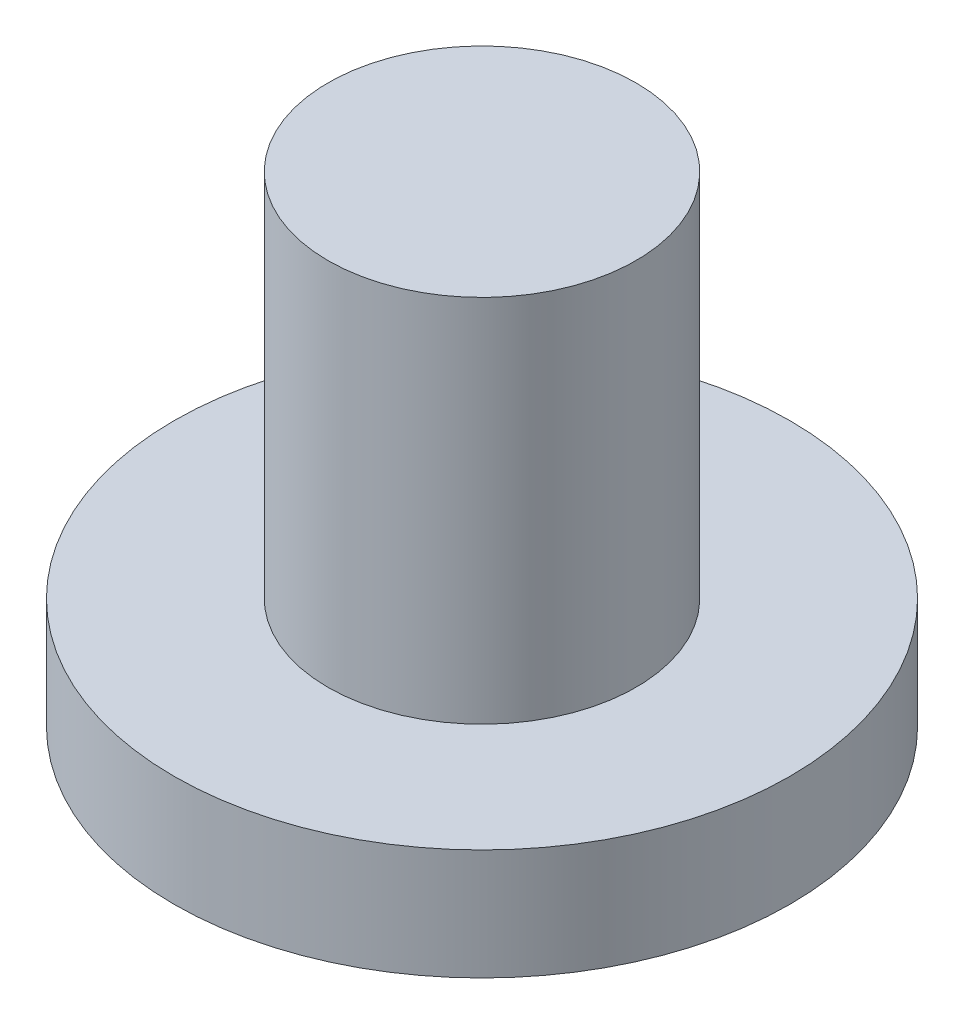
SolidWorks part; units mm, degrees
ref_plane "前视基准面" through (0, 0, 0) normal (0, 0, 1) x (1, 0, 0)
ref_plane "上视基准面" through (0, 0, 0) normal (0, 1, 0) x (1, 0, 0)
ref_plane "右视基准面" through (0, 0, 0) normal (1, 0, 0) x (0, 0, -1)
other "Configuration Table"
sketch "草图1" plane through (0, 0, 0) normal (0, 1, 0) x (1, 0, 0)
  circle A0 centre (0, 0) radius 2.5
  dimension "D1" = 5
extrude "凸台-拉伸1" add sketch "草图1" along normal blind 0.9
sketch "草图2" plane through (0, 0.9, 0) normal (0, 1, 0) x (1, 0, 0)
  circle A0 centre (0, 0) radius 1.25
  dimension "D1" = 2.5
extrude "凸台-拉伸2" add sketch "草图2" along normal blind 3
sketch "草图3" plane through (0, 0, 0) normal (0, -1, 0) x (1, 0, 0)
  line L1 (0.433, 0.75) -> (-0.433, 0.75)
  line L2 (-0.433, 0.75) -> (-0.866, 0)
  line L3 (-0.866, 0) -> (-0.433, -0.75)
  line L4 (-0.433, -0.75) -> (0.433, -0.75)
  line L5 (0.433, -0.75) -> (0.866, 0)
  line L6 (0.866, 0) -> (0.433, 0.75)
  circle A0 centre (0, 0) radius 0.866 construction
  dimension "D1" = 1.5
extrude "切除-拉伸1" cut sketch "草图3" against normal blind 0.5
